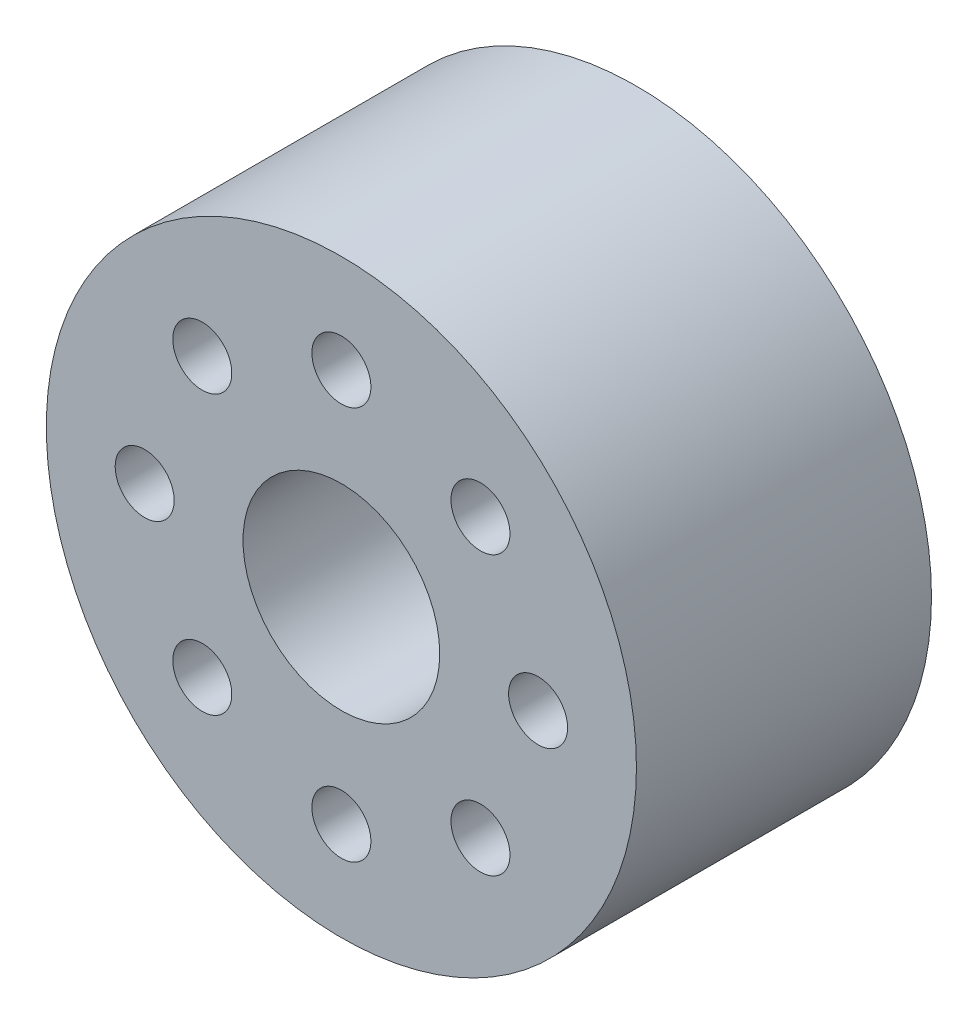
SolidWorks part; units mm, degrees
ref_plane "Front Plane" through (0, 0, 0) normal (0, 0, 1) x (1, 0, 0)
ref_plane "Top Plane" through (0, 0, 0) normal (0, 1, 0) x (1, 0, 0)
ref_plane "Right Plane" through (0, 0, 0) normal (1, 0, 0) x (0, 0, -1)
sketch "Sketch1" plane through (0, 0, 0) normal (0, 0, 1) x (1, 0, 0)
  circle A0 centre (0, 0) radius 12
  dimension "D1" = 24
extrude "Boss-Extrude1" add sketch "Sketch1" along normal blind 12
sketch "Sketch4" plane through (0, 0, 12) normal (0, 0, 1) x (1, 0, 0)
  point P0 (0, 0)
hole_wizard "Ø8.0mm Dowel Hole1" positions "Sketch4" profile "Sketch3" hole size "Ø8.0" standard "DIN" end condition through all
sketch "Sketch3" plane through (0, 0, 12) normal (1, 0, 0) x (0, -1, 0)
  line L0 (0, 0) -> (0, 12)
  line L1 (0, 12) -> (4, 12)
  line L2 (4, 12) -> (4, 0)
  line L5 (4, 0) -> (0, 0)
  line L11 (0, -6.35) -> (0, 107.95) construction
  dimension "Thru Hole Dia." = 8
  dimension "Thru Hole Depth" = 12
sketch "Sketch7" plane through (0, 0, 0) normal (0, 0, 1) x (1, 0, 0)
  circle A0 centre (0, 0) radius 8
  point P5 (0, 8)
  point P11 (5.6569, 5.6569)
  point P12 (8, 0)
  point P13 (5.6569, -5.6569)
  point P14 (0, -8)
  point P15 (-5.6569, -5.6569)
  point P16 (-8, 0)
  point P17 (-5.6569, 5.6569)
  dimension "D1" = 16
  dimension "D2" = 8
hole_wizard "CBORE for M2 Hex Socket Head Cap Screw1" positions "Sketch7" profile "Sketch8" counterbore size "M2" standard "DIN" end condition through all
sketch "Sketch8" plane through (-5.6569, 5.6569, 0) normal (1, 0, 0) x (0, 1, 0)
  line L0 (0, 0) -> (0, 12)
  line L1 (0, 12) -> (1.2, 12)
  line L3 (1.2, 12) -> (1.2, 5.5)
  line L4 (1.2, 5.5) -> (2.2, 5.5)
  line L5 (2.2, 5.5) -> (2.2, 0)
  line L7 (2.2, 0) -> (0, 0)
  line L11 (0, -6.35) -> (0, 107.95) construction
  dimension "Thru Hole Dia." = 2.4
  dimension "Thru Hole Depth" = 12
  dimension "C'Bore Dia." = 4.4
  dimension "C'Bore Depth" = 5.5
